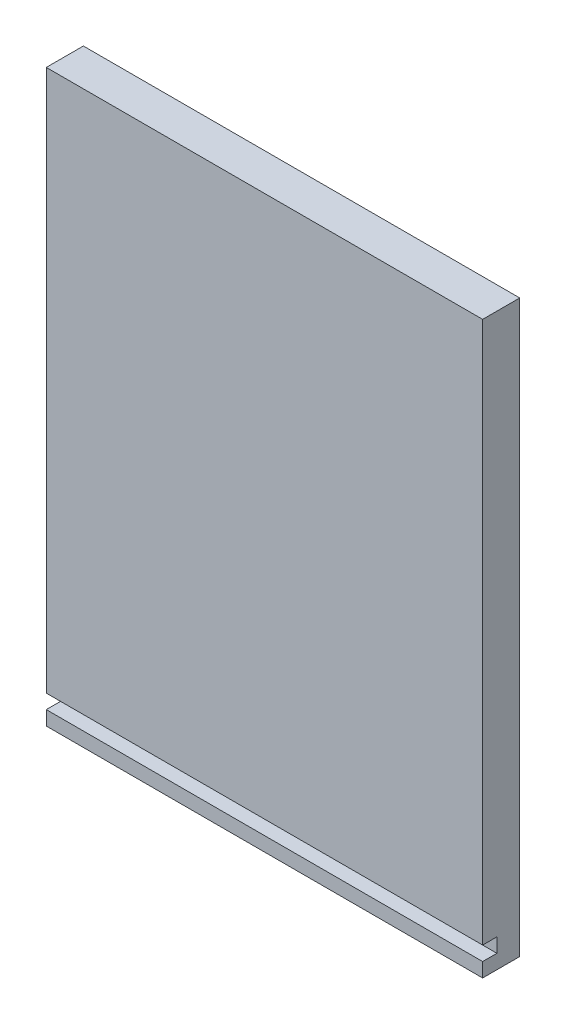
SolidWorks part; units mm, degrees
ref_plane "正面" through (0, 0, 0) normal (0, 0, 1) x (1, 0, 0)
ref_plane "平面" through (0, 0, 0) normal (0, 1, 0) x (1, 0, 0)
ref_plane "右側面" through (0, 0, 0) normal (1, 0, 0) x (0, 0, -1)
sketch "ｽｹｯﾁ1" plane through (0, 0, 0) normal (0, 0, 1) x (1, 0, 0)
  line L1 (-53.9801, 133.3357) -> (99.0199, 133.3357)
  line L2 (-53.9801, 133.3357) -> (-53.9801, -66.6643)
  line L3 (-53.9801, -66.6643) -> (99.0199, -66.6643)
  line L4 (99.0199, 133.3357) -> (99.0199, -66.6643)
  dimension "D3" = 200
  dimension "D4" = 153
extrude "ﾎﾞｽ - 押し出し1" add sketch "ｽｹｯﾁ1" along normal blind 13
sketch "ｽｹｯﾁ2" plane through (0, 0, 13) normal (0, 0, 1) x (1, 0, 0)
  line L1 (-53.9801, -56.6643) -> (99.0199, -56.6643)
  line L2 (-53.9801, -56.6643) -> (-53.9801, -61.6643)
  line L3 (-53.9801, -61.6643) -> (99.0199, -61.6643)
  line L4 (99.0199, -56.6643) -> (99.0199, -61.6643)
  line L5 (99.0199, -66.6643) -> (99.0199, 133.3357) construction
  line L7 (-53.9801, -66.6643) -> (99.0199, -66.6643) construction
  line L9 (-53.9801, 133.3357) -> (-53.9801, -66.6643) construction
  dimension "D1" = 5
  dimension "D2" = 153
  dimension "D3" = 5
extrude "ｶｯﾄ - 押し出し1" cut sketch "ｽｹｯﾁ2" against normal blind 5
